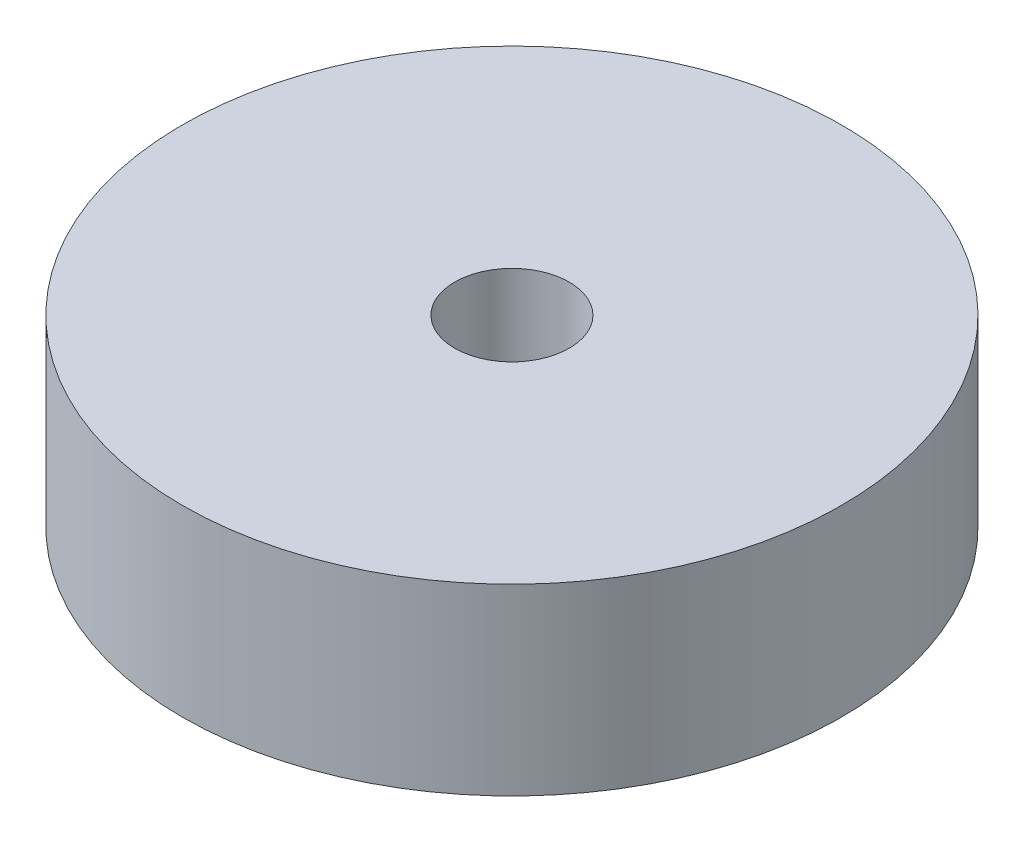
SolidWorks part; units mm, degrees
ref_plane "Front Plane" through (0, 0, 0) normal (0, 0, 1) x (1, 0, 0)
ref_plane "Top Plane" through (0, 0, 0) normal (0, 1, 0) x (1, 0, 0)
ref_plane "Right Plane" through (0, 0, 0) normal (1, 0, 0) x (0, 0, -1)
sketch "Sketch1" plane through (0, 0, 0) normal (0, 1, 0) x (1, 0, 0)
  circle A0 centre (0, 0) radius 36.5125
  circle A1 centre (0, 0) radius 6.35
  dimension "D1" = 12.7
  dimension "D2" = 73.025
extrude "Boss-Extrude1" add sketch "Sketch1" along normal blind 20.32
